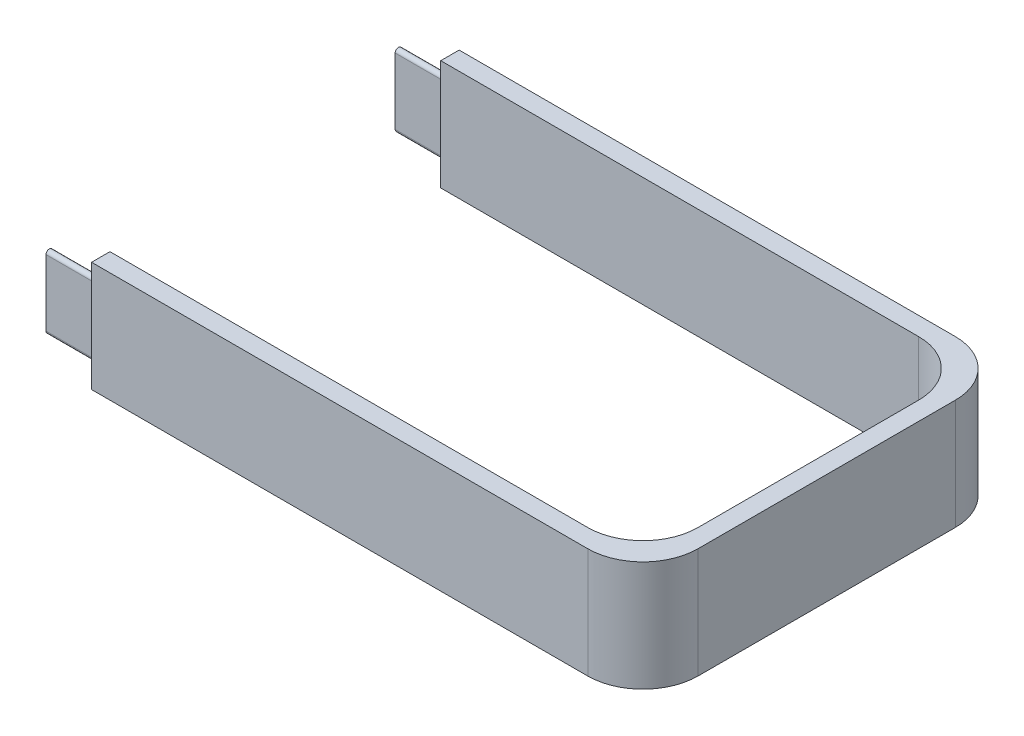
SolidWorks part; units mm, degrees
material "ABS"
ref_plane "Front Plane" through (0, 0, 0) normal (0, 0, 1) x (1, 0, 0)
ref_plane "Top Plane" through (0, 0, 0) normal (0, 1, 0) x (1, 0, 0)
ref_plane "Right Plane" through (0, 0, 0) normal (1, 0, 0) x (0, 0, -1)
sketch "Sketch1" plane through (0, 0, 0) normal (0, 1, 0) x (1, 0, 0)
  line L1 (0, 0) -> (305, 0)
  line L2 (0, 0) -> (0, 97.5)
  line L3 (2.5, 100) -> (305, 100)
  line L4 (320, 15) -> (320, 85)
  line L5 (20, 95) -> (300, 95)
  line L6 (5, 80) -> (5, 20)
  line L7 (20, 5) -> (300, 5)
  line L8 (315, 80) -> (315, 20)
  arc A0 (20, 5) -> (5, 20) centre (20, 20) cw
  arc A1 (5, 80) -> (20, 95) centre (20, 80) cw
  arc A2 (300, 95) -> (315, 80) centre (300, 80) cw
  arc A3 (315, 20) -> (300, 5) centre (300, 20) cw
  arc A4 (305, 0) -> (320, 15) centre (305, 15) ccw
  arc A5 (320, 85) -> (305, 100) centre (305, 85) ccw
  arc A6 (0, 97.5) -> (2.5, 100) centre (2.5, 97.5) cw
  dimension "D1" = 15
  dimension "D2" = 2.5
extrude "Boss-Extrude1" add sketch "Sketch1" along normal blind 30
ref_plane "Plane1" through (0, 0, -50) normal (0, 0, 1) x (1, 0, 0)
sketch "Sketch2" plane through (0, 0, -50) normal (0, 0, 1) x (1, 0, 0)
  line L0 (315, 0) -> (315, 5)
  line L1 (315, 30) -> (315, 0) construction
  line L2 (315, 5) -> (312.5, 2.5)
  line L3 (312.5, 2.5) -> (315, 0)
extrude "Boss-Extrude2" add sketch "Sketch2" along normal blind 10 and the other way blind 10
sketch "Sketch3" plane through (0, 0, 0) normal (0, 1, 0) x (1, 0, 0)
  line L0 (0, 0) -> (170, 0)
  line L1 (0, 0) -> (305, 0) construction
  line L2 (170, 0) -> (170, 100)
  line L3 (305, 100) -> (2.5, 100) construction
  line L4 (170, 100) -> (0, 100)
  line L5 (0, 100) -> (0, 0)
extrude "Cut-Extrude1" cut sketch "Sketch3" along normal blind 40
ref_plane "Plane2" through (170, 0, 0) normal (1, 0, 0) x (0, 0, -1)
sketch "Sketch4" plane through (170, 0, 0) normal (1, 0, 0) x (0, 0, -1)
  line L0 (97.5, 30) -> (97.5, 0)
  line L1 (95, 30) -> (100, 30) construction
  line L2 (95, 0) -> (100, 0) construction
  line L3 (2.5, 30) -> (2.5, 0)
  line L4 (0, 30) -> (5, 30) construction
  line L5 (0, 0) -> (5, 0) construction
  line L6 (97.5, 6) -> (97.5, 24) construction
  line L7 (96.6, 6) -> (96.6, 24)
  line L8 (98.4, 6) -> (98.4, 24)
  line L9 (2.5, 6) -> (2.5, 24) construction
  line L10 (1.6, 6) -> (1.6, 24)
  line L11 (3.4, 6) -> (3.4, 24)
  arc A0 (96.6, 6) -> (98.4, 6) centre (97.5, 6) ccw
  arc A1 (98.4, 24) -> (96.6, 24) centre (97.5, 24) ccw
  arc A2 (1.6, 6) -> (3.4, 6) centre (2.5, 6) ccw
  arc A3 (3.4, 24) -> (1.6, 24) centre (2.5, 24) ccw
  point P14 (97.5, 15)
  point P21 (2.5, 15)
extrude "Boss-Extrude3" add sketch "Sketch4" against normal blind 14 contours L8 A1 L0 A0 | L0 A1 L7 A0 | L11 A3 L3 A2 | L3 A3 L10 A2
